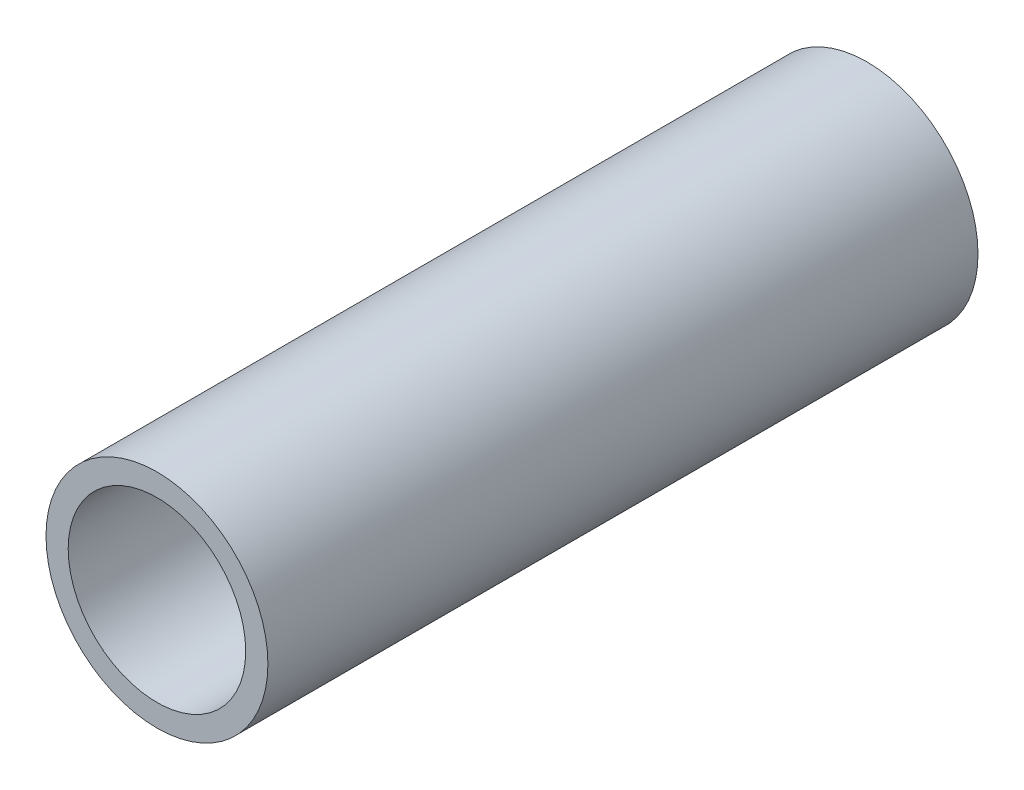
SolidWorks part; units mm, degrees
ref_plane "Front Plane" through (0, 0, 0) normal (0, 0, 1) x (1, 0, 0)
ref_plane "Top Plane" through (0, 0, 0) normal (0, 1, 0) x (1, 0, 0)
ref_plane "Right Plane" through (0, 0, 0) normal (1, 0, 0) x (0, 0, -1)
sketch "Sketch1" plane through (0, 0, 0) normal (0, 0, 1) x (1, 0, 0)
  circle A0 centre (0, 0) radius 3.9688
  circle A1 centre (0, 0) radius 3.175
  dimension "D1" = 6.35
  dimension "D2" = 7.9375
extrude "Boss-Extrude1" add sketch "Sketch1" along normal blind 25.4
